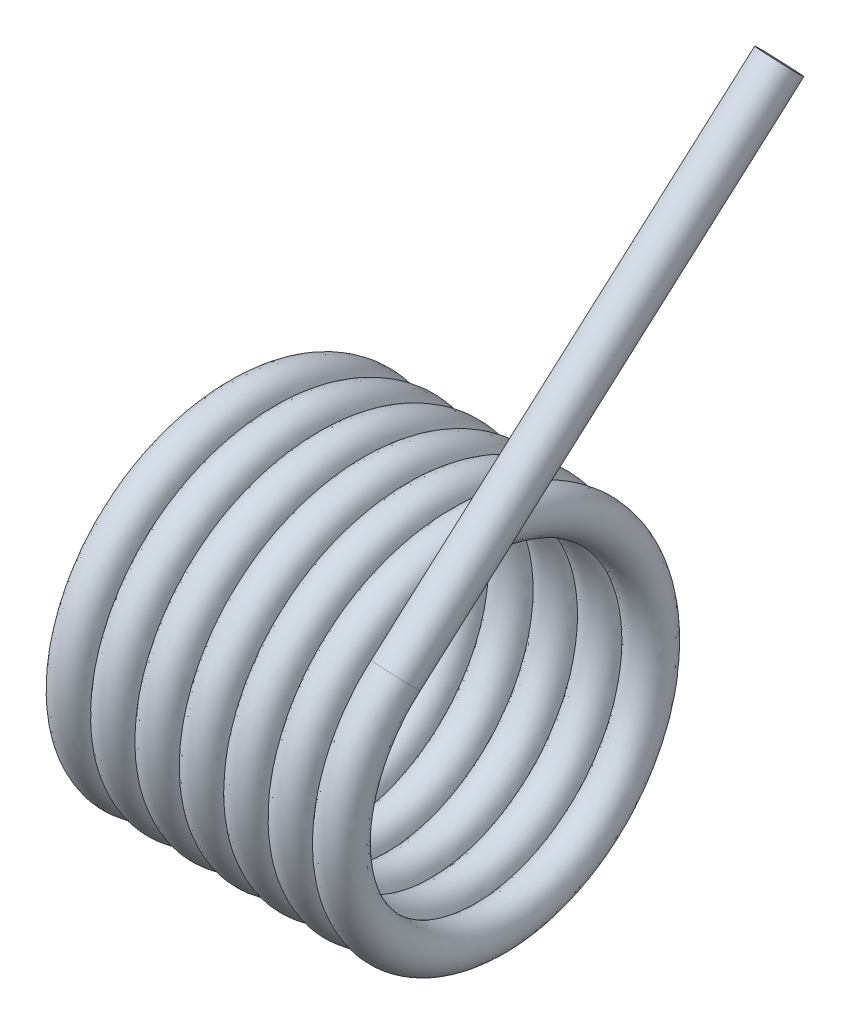
SolidWorks part; units mm, degrees
ref_plane "Front" through (0, 0, 0) normal (0, 0, 1) x (1, 0, 0)
ref_plane "Top" through (0, 0, 0) normal (0, 1, 0) x (1, 0, 0)
ref_plane "Right" through (0, 0, 0) normal (1, 0, 0) x (0, 0, -1)
sketch "Sketch1" plane through (0, 0, 0) normal (1, 0, 0) x (0, 0, -1)
  line L0 (0, 0) -> (0, -1.0795) construction
  line L1 (0, -1.0795) -> (0, -1.2319) construction
  line L2 (0, -1.2319) -> (0, -1.3843) construction
  circle A0 centre (0, 0) radius 1.0795 construction
  circle A1 centre (0, 0) radius 1.3843 construction
  circle A2 centre (0, 0) radius 1.2319
  circle A3 centre (0, -1.2319) radius 0.1524 construction
  circle A4 centre (0, 0) radius 0.8509 construction
curve "Helix/Spiral1" pitch 0.3302 height 2.105 turns 6.375
ref_plane "Plane1" through (0, -1.2319, 0) normal (0.0426, 0, 0.9991) x (0.9991, 0, -0.0426)
sketch "Sketch2" plane through (0, -1.2319, 0) normal (0.0426, 0, 0.9991) x (0.9991, 0, -0.0426)
  circle A0 centre (0, 0) radius 0.1524
  dimension "D1" = 0.3048
sweep "Sweep1" add profiles "Sketch2" path "Helix/Spiral1"
sketch "Sketch3" plane through (0, 0, 0) normal (-0.0426, 0, -0.9991) x (-0.9991, 0, 0.0426)
  circle A1 centre (0, -1.2319) radius 0.1524
  circle A2 centre (0, -1.2319) radius 0.1524
  dimension "D1" = 0
extrude "Extrude1" add sketch "Sketch3" along normal blind 2.54
sketch "Sketch4" plane through (0.0038, 0.0634, -0.0634) normal (0.0426, 0.7065, -0.7065) x (0.992, -0.1141, -0.0543)
  circle A1 centre (1.9415, -1.4736) radius 0.1524
  circle A2 centre (1.9415, -1.4736) radius 0.1524
  dimension "D1" = 0
extrude "Extrude2" add sketch "Sketch4" along normal blind 3.81
sketch "Sketch5" plane through (0, 0, 0) normal (1, 0, 0) x (0, 0, -1)
  circle A0 centre (0, 0) radius 0.8509 construction
  circle A1 centre (0, 0) radius 0.8509
equation "\"D4@Helix/Spiral1\"=\"Wire Dia@Sketch1\"+.001"
equation "\"D1@Sketch2\"=\"Wire Dia@Sketch1\""
